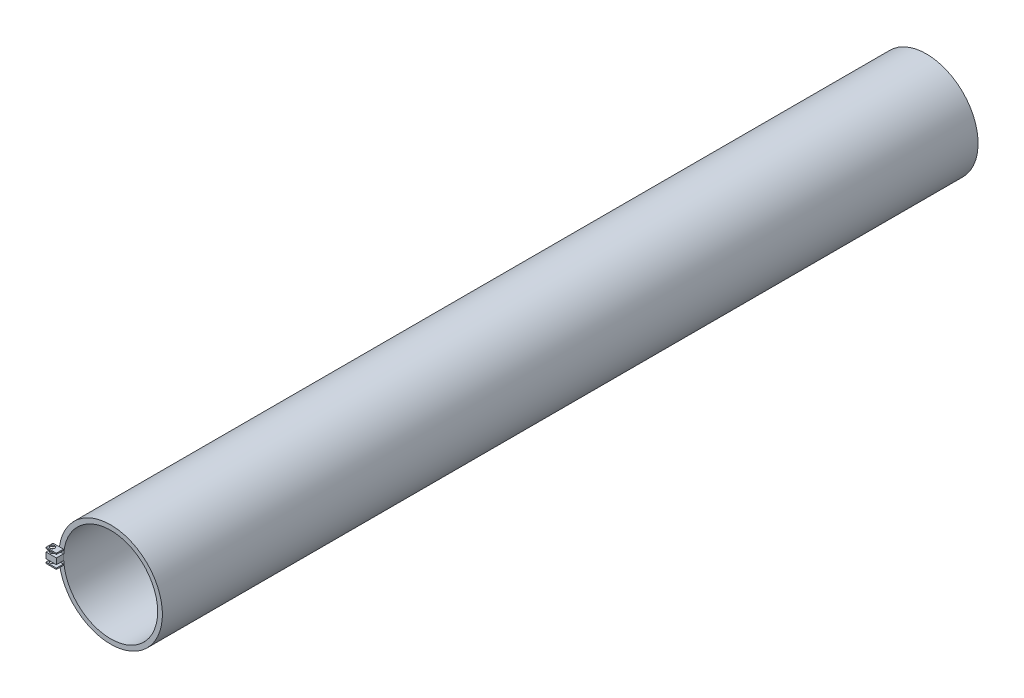
SolidWorks part; units mm, degrees
ref_plane "Front Plane" through (0, 0, 0) normal (0, 0, 1) x (1, 0, 0)
ref_plane "Top Plane" through (0, 0, 0) normal (0, 1, 0) x (1, 0, 0)
ref_plane "Right Plane" through (0, 0, 0) normal (1, 0, 0) x (0, 0, -1)
sketch "Sketch1" plane through (0, 0, 0) normal (0, 0, 1) x (1, 0, 0)
  circle A0 centre (0, 0) radius 22
  circle A1 centre (0, 0) radius 20
  dimension "D1" = 44
  dimension "D2" = 40
extrude "Boss-Extrude1" add sketch "Sketch1" along normal blind 350
sketch "Sketch2" plane through (0, 0, 0) normal (0, 0, -1) x (-1, 0, 0)
  line L0 (0, 0) -> (22, 0) construction
  line L1 (21.177, 3) -> (21.177, -3)
  line L2 (24.5, 3) -> (21.177, 3)
  line L3 (24.5, 3) -> (24.5, -3)
  line L4 (24.5, -3) -> (21.177, -3)
  line L5 (21.177, 2.5) -> (24.5, 2.5)
  line L6 (24.5, 3) -> (21.177, -0.9876) construction
  line L7 (24.5, -3) -> (21.177, 0.9876) construction
  line L8 (21.177, 1.25) -> (24.5, 1.25)
  line L9 (21.177, -1.25) -> (24.5, -1.25)
  line L10 (21.177, -2.5) -> (24.5, -2.5)
  circle A0 centre (0, 0) radius 22 construction
  point P16 (22.8385, 3)
  circle M8 centre (0, 0) radius 22
  dimension "D1" = 1.25
  dimension "D2" = 6
  dimension "D3" = 2.5
  dimension "D4" = 0.5
extrude "Boss-Extrude2" add sketch "Sketch2" against normal blind 3 contours L5 L3 L2 M8 | L9 L3 L8 M8 | L10 L4 L3 M8
sketch "Sketch3" plane through (0, 3, 0) normal (0, 1, 0) x (1, 0, 0)
  line L0 (-24.5, -1.5) -> (-21.7945, -1.5) construction
  line L1 (-24.5, -3) -> (-24.5, 0) construction
  line L2 (-21.7945, -3) -> (-21.7945, 0) construction
  circle A0 centre (-23.1472, -1.5) radius 1
  dimension "D1" = 2
extrude "Cut-Extrude1" cut sketch "Sketch3" against normal through all both and the other way through all
sketch "Sketch4" plane through (0, 0, 350) normal (0, 0, 1) x (1, 0, 0)
  line L0 (-21.6626, 1.25) -> (-21.6626, -1.25)
  line L1 (-21.6626, 1.25) -> (-24.5, 1.25)
  line L3 (-21.6626, -1.25) -> (-24.5, -1.25)
  line L4 (-24.5, 1.25) -> (-24.5, -1.25)
  line L5 (-21.6626, 0.1687) -> (-24.5, -1.25) construction
  line L6 (-21.6626, -0.1687) -> (-24.5, 1.25) construction
  line L7 (-21.7945, 3) -> (-24.5, 3)
  line L8 (-21.7945, 3) -> (-21.7945, 2.5)
  line L9 (-21.7945, 2.5) -> (-24.5, 2.5)
  line L10 (-24.5, 3) -> (-24.5, 2.5)
  line L11 (-21.7945, -3) -> (-24.5, -3)
  line L12 (-21.7945, -3) -> (-21.7945, -2.5)
  line L13 (-21.7945, -2.5) -> (-24.5, -2.5)
  line L14 (-24.5, -3) -> (-24.5, -2.5)
  arc A0 (-21.9645, 1.25) -> (-21.9645, -1.25) centre (0, 0) ccw construction
  point P0 (-22, 0)
extrude "Boss-Extrude3" add sketch "Sketch4" against normal blind 3
sketch "Sketch5" plane through (0, 3, 0) normal (0, 1, 0) x (1, 0, 0)
  line L0 (-24.5, -348.5) -> (-21.7945, -348.5) construction
  line L1 (-24.5, -347) -> (-24.5, -350) construction
  line L2 (-21.7945, -347) -> (-21.7945, -350) construction
  circle A0 centre (-23.1472, -348.5) radius 1
  dimension "D1" = 2
extrude "Cut-Extrude2" cut sketch "Sketch5" against normal through all both and the other way through all
sketch "Sketch6" plane through (0, 0, 350) normal (0, 0, 1) x (1, 0, 0)
  circle A0 centre (0, 0) radius 22
extrude "Cut-Extrude3" cut sketch "Sketch6" against normal blind 3
sketch "Sketch7" plane through (-24.5, 0, 0) normal (-1, 0, 0) x (0, 0, 1)
  line L0 (350, 0) -> (347, 0) construction
  line L1 (350, -1.25) -> (350, 1.25) construction
  line L2 (347, 1.25) -> (347, -1.25) construction
  line L4 (347, -3) -> (350, -3)
  line L5 (347, -3) -> (347, 3)
  line L6 (347, 3) -> (350, 3)
  line L7 (350, -3) -> (350, 3)
  line L8 (347, -3) -> (350, 3) construction
  line L9 (347, 3) -> (350, -3) construction
  point P6 (348.5, 0)
extrude "Boss-Extrude4" add sketch "Sketch7" against normal blind 4.4
sketch "Sketch8" plane through (0, 3, 0) normal (0, 1, 0) x (1, 0, 0)
  line L0 (-24.5, -348.5) -> (-20.4712, -348.5) construction
  line L1 (-24.5, -350) -> (-24.5, -347) construction
  line L2 (-21.7945, -347) -> (-21.7945, -350) construction
  line L3 (-20.1, -350) -> (-24.5, -350) construction
  circle A0 centre (-23.25, -348.5) radius 1
  dimension "D1" = 2
  dimension "D2" = 1.25
extrude "Cut-Extrude4" cut sketch "Sketch8" against normal through all both and the other way through all
sketch "Sketch9" plane through (-24.5, 0, 0) normal (-1, 0, 0) x (0, 0, 1)
  line L0 (347, 0) -> (350, 0) construction
  line L1 (347, 3) -> (347, -3) construction
  line L2 (350, -3) -> (350, 3) construction
  line L3 (347, 2.5) -> (350, 2.5)
  line L4 (347, 3) -> (347, -3) construction
  line L5 (347, 1.25) -> (350, 1.25)
  line L6 (347, -1.25) -> (350, -1.25)
  line L7 (347, -2.5) -> (350, -2.5)
  line L8 (350, 2.5) -> (350, 1.25)
  line L9 (347, 2.5) -> (347, 1.25)
  line L10 (350, -2.5) -> (350, -1.25)
  line L11 (347, -2.5) -> (347, -1.25)
  dimension "D1" = 1.25
  dimension "D2" = 2.5
extrude "Cut-Extrude5" cut sketch "Sketch9" against normal blind 4.4
